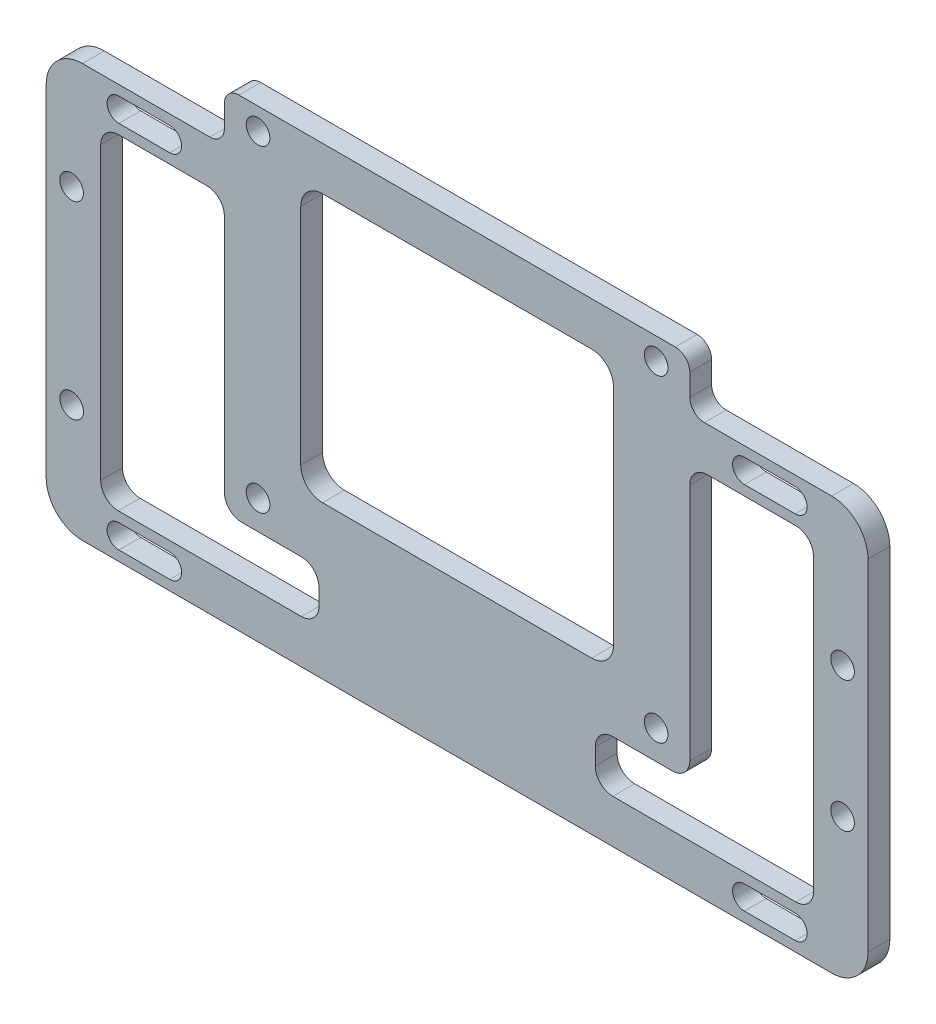
SolidWorks part; units mm, degrees
material "PBT 一般用途"
ref_plane "前视基准面" through (0, 0, 0) normal (0, 0, 1) x (1, 0, 0)
ref_plane "上视基准面" through (0, 0, 0) normal (0, 1, 0) x (1, 0, 0)
ref_plane "右视基准面" through (0, 0, 0) normal (1, 0, 0) x (0, 0, -1)
other "Configuration Table"
sketch "草图1" plane through (0, 0, 0) normal (0, 0, 1) x (1, 0, 0)
  line L0 (-53.8141, 0) -> (49.1859, 0)
  line L1 (-58.8141, 5) -> (-58.8141, 51.8)
  line L2 (-53.8141, 56.8) -> (-36.3141, 56.8)
  line L3 (-34.3141, 58.8) -> (-34.3141, 61.8)
  line L4 (-32.3141, 63.8) -> (27.6859, 63.8)
  line L5 (29.6859, 61.8) -> (29.6859, 58.8)
  line L6 (31.6859, 56.8) -> (49.1859, 56.8)
  line L7 (54.1859, 51.8) -> (54.1859, 5)
  arc A0 (54.1859, 51.8) -> (49.1859, 56.8) centre (49.1859, 51.8) ccw
  arc A1 (49.1859, 0) -> (54.1859, 5) centre (49.1859, 5) ccw
  arc A2 (-53.8141, 0) -> (-58.8141, 5) centre (-53.8141, 5) cw
  arc A3 (-58.8141, 51.8) -> (-53.8141, 56.8) centre (-53.8141, 51.8) cw
  arc A4 (31.6859, 56.8) -> (29.6859, 58.8) centre (31.6859, 58.8) cw
  arc A5 (29.6859, 61.8) -> (27.6859, 63.8) centre (27.6859, 61.8) ccw
  arc A6 (-34.3141, 61.8) -> (-32.3141, 63.8) centre (-32.3141, 61.8) cw
  arc A7 (-36.3141, 56.8) -> (-34.3141, 58.8) centre (-36.3141, 58.8) ccw
  point P11 (54.1859, 56.8)
  point P14 (54.1859, 0)
  point P17 (-58.8141, 0)
  point P20 (-58.8141, 56.8)
  point P23 (29.6859, 56.8)
  point P26 (29.6859, 63.8)
  point P29 (-34.3141, 63.8)
  point P32 (-34.3141, 56.8)
  dimension "D7" = 5
  dimension "D8" = 2
  dimension "D1" = 113
  dimension "D2" = 64
  dimension "D3" = 24.5
  dimension "D4" = 24.5
  dimension "D5" = 56.8
  dimension "D6" = 7
  dimension "D9" = 56.8
extrude "凸台-拉伸2" add sketch "草图1" along normal blind 3 contours L2 A7 L3 A6 L4 A5 L5 A4 L6 A0 L7 A1 L0 A2 L1 A3
sketch "草图5" plane through (0, 0, 3) normal (0, 0, 1) x (1, 0, 0)
  line L0 (-34.3141, 58.8) -> (-34.3141, 61.8) construction
  line L1 (-48.9062, 50.8) -> (-36.722, 50.8)
  line L2 (-32.3141, 63.8) -> (27.6859, 63.8) construction
  line L3 (29.6859, 61.8) -> (29.6859, 58.8) construction
  line L4 (-53.8141, 0) -> (49.1859, 0) construction
  line L5 (-58.8141, 5) -> (-58.8141, 51.8) construction
  line L6 (54.1859, 51.8) -> (54.1859, 5) construction
  line L7 (-48.8141, 3) -> (-41.8141, 3) construction
  line L8 (-48.8141, 4.625) -> (-41.8141, 4.625)
  line L9 (-48.8141, 1.375) -> (-41.8141, 1.375)
  line L10 (37.1859, 3) -> (44.1859, 3) construction
  line L11 (37.1859, 4.625) -> (44.1859, 4.625)
  line L12 (37.1859, 1.375) -> (44.1859, 1.375)
  line L13 (-48.8141, 53.8) -> (-41.8141, 53.8) construction
  line L14 (-48.8141, 55.425) -> (-41.8141, 55.425)
  line L15 (-48.8141, 52.175) -> (-41.8141, 52.175)
  line L16 (37.1859, 53.8) -> (44.1859, 53.8) construction
  line L17 (37.1859, 55.425) -> (44.1859, 55.425)
  line L18 (37.1859, 52.175) -> (44.1859, 52.175)
  line L19 (-51.3141, 48.3921) -> (-51.3141, 8.4079)
  line L20 (-34.3141, 48.3921) -> (-34.3141, 15.5179)
  line L21 (-48.9062, 6) -> (-23.722, 6)
  line L22 (-21.3141, 8.4079) -> (-21.3141, 10.7021)
  line L23 (-23.722, 13.11) -> (-31.9062, 13.11)
  line L24 (29.6859, 48.3921) -> (29.6859, 15.5179)
  line L25 (27.278, 13.11) -> (19.0938, 13.11)
  line L26 (16.6859, 10.7021) -> (16.6859, 8.4079)
  line L27 (19.0938, 6) -> (44.278, 6)
  line L28 (46.6859, 8.4079) -> (46.6859, 48.3921)
  line L29 (44.278, 50.8) -> (32.0938, 50.8)
  line L30 (-23.8141, 54.8) -> (-23.8141, 24)
  line L31 (-20.8141, 21) -> (16.1859, 21)
  line L32 (19.1859, 24) -> (19.1859, 54.8)
  line L33 (16.1859, 57.8) -> (-20.8141, 57.8)
  circle A0 centre (-29.6841, 60.8) radius 1.625
  circle A1 centre (25.0559, 60.8) radius 1.625
  circle A2 centre (-29.6841, 17.11) radius 1.625
  circle A3 centre (25.0559, 17.11) radius 1.625
  circle A4 centre (-55.3141, 15.4) radius 1.625
  circle A5 centre (-55.3141, 41.4) radius 1.625
  circle A6 centre (50.6859, 37.4) radius 1.625
  circle A7 centre (50.6859, 19.4) radius 1.625
  arc A8 (-48.8141, 4.625) -> (-48.8141, 1.375) centre (-48.8141, 3) ccw
  arc A9 (-41.8141, 1.375) -> (-41.8141, 4.625) centre (-41.8141, 3) ccw
  arc A10 (37.1859, 4.625) -> (37.1859, 1.375) centre (37.1859, 3) ccw
  arc A11 (44.1859, 1.375) -> (44.1859, 4.625) centre (44.1859, 3) ccw
  arc A12 (-48.8141, 55.425) -> (-48.8141, 52.175) centre (-48.8141, 53.8) ccw
  arc A13 (-41.8141, 52.175) -> (-41.8141, 55.425) centre (-41.8141, 53.8) ccw
  arc A14 (37.1859, 55.425) -> (37.1859, 52.175) centre (37.1859, 53.8) ccw
  arc A15 (44.1859, 52.175) -> (44.1859, 55.425) centre (44.1859, 53.8) ccw
  arc A16 (-51.3141, 8.4079) -> (-48.9062, 6) centre (-48.9062, 8.4079) ccw
  arc A17 (-23.722, 6) -> (-21.3141, 8.4079) centre (-23.722, 8.4079) ccw
  arc A18 (-21.3141, 10.7021) -> (-23.722, 13.11) centre (-23.722, 10.7021) ccw
  arc A19 (-31.9062, 13.11) -> (-34.3141, 15.5179) centre (-31.9062, 15.5179) cw
  arc A20 (-34.3141, 48.3921) -> (-36.722, 50.8) centre (-36.722, 48.3921) ccw
  arc A21 (-51.3141, 48.3921) -> (-48.9062, 50.8) centre (-48.9062, 48.3921) cw
  arc A22 (44.278, 50.8) -> (46.6859, 48.3921) centre (44.278, 48.3921) cw
  arc A23 (46.6859, 8.4079) -> (44.278, 6) centre (44.278, 8.4079) cw
  arc A24 (19.0938, 6) -> (16.6859, 8.4079) centre (19.0938, 8.4079) cw
  arc A25 (16.6859, 10.7021) -> (19.0938, 13.11) centre (19.0938, 10.7021) cw
  arc A26 (27.278, 13.11) -> (29.6859, 15.5179) centre (27.278, 15.5179) ccw
  arc A27 (29.6859, 48.3921) -> (32.0938, 50.8) centre (32.0938, 48.3921) cw
  arc A28 (16.1859, 57.8) -> (19.1859, 54.8) centre (16.1859, 54.8) cw
  arc A29 (19.1859, 24) -> (16.1859, 21) centre (16.1859, 24) cw
  arc A30 (-20.8141, 21) -> (-23.8141, 24) centre (-20.8141, 24) cw
  arc A31 (-23.8141, 54.8) -> (-20.8141, 57.8) centre (-20.8141, 54.8) cw
  point P0 (-29.6841, 60.8)
  point P7 (25.0559, 60.8)
  point P12 (-29.6841, 17.11)
  point P13 (25.0559, 17.11)
  point P18 (-55.3141, 15.4)
  point P23 (-55.3141, 41.4)
  point P24 (50.6859, 19.4)
  point P27 (50.6859, 37.4)
  point P37 (-45.3141, 3)
  point P45 (40.6859, 3)
  point P52 (-45.3141, 53.8)
  point P59 (40.6859, 53.8)
  dimension "D4" = 43.69
  dimension "D6" = 3
  dimension "D13" = 10
  dimension "D30" = 2.4079
  dimension "D34" = 2.4079
  dimension "D41" = 3
  dimension "D15" = 3.5
  dimension "D1" = 4.63
  dimension "D2" = 3
  dimension "D3" = 4.63
  dimension "D5" = 43.69
  dimension "D7" = 15.4
  dimension "D8" = 3.5
  dimension "D9" = 26
  dimension "D10" = 19.4
  dimension "D11" = 3.5
  dimension "D12" = 18
  dimension "D14" = 7
  dimension "D16" = 3
  dimension "D17" = 50.8
  dimension "D18" = 0
  dimension "D19" = 7
  dimension "D20" = 10
  dimension "D21" = 7
  dimension "D22" = 3
  dimension "D23" = 3.5
  dimension "D24" = 50.8
  dimension "D25" = 4
  dimension "D26" = 7
  dimension "D27" = 0
  dimension "D28" = 3
  dimension "D29" = 4
  dimension "D31" = 3
  dimension "D32" = 30
  dimension "D33" = 30
  dimension "D35" = 4
  dimension "D36" = 4
  dimension "D37" = 6
  dimension "D38" = 35
  dimension "D39" = 35
  dimension "D40" = 21
  dimension "D42" = 0
extrude "切除-拉伸3" cut sketch "草图5" against normal blind 3
